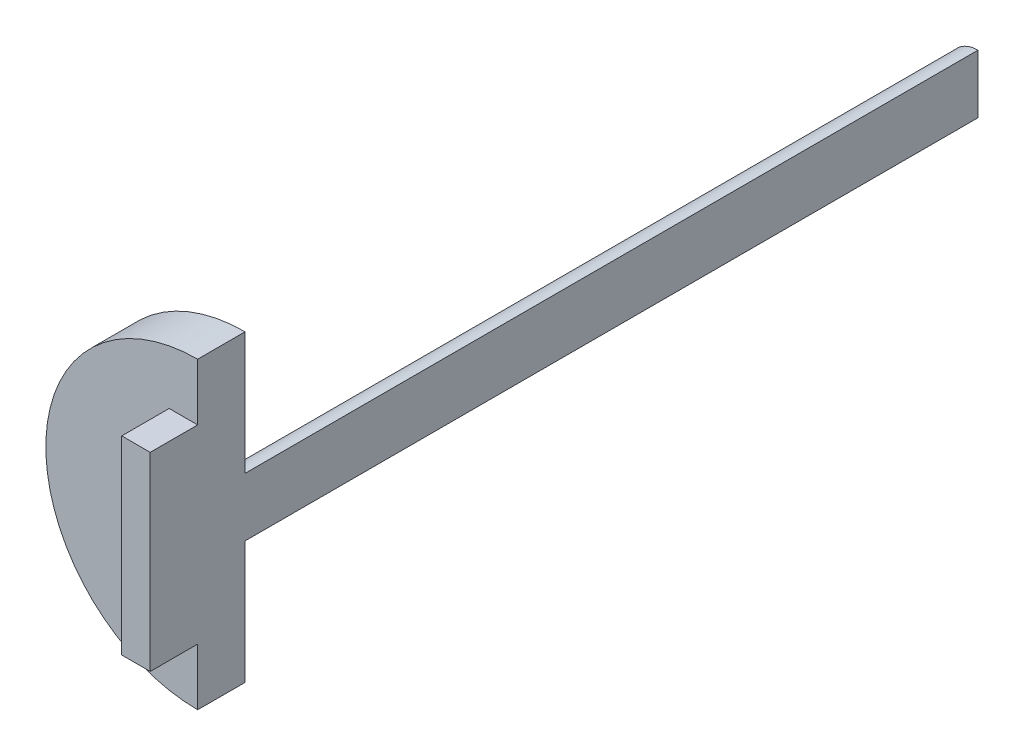
SolidWorks part; units mm, degrees
ref_plane "Plano frontal" through (0, 0, 0) normal (0, 0, 1) x (1, 0, 0)
ref_plane "Plano superior" through (0, 0, 0) normal (0, 1, 0) x (1, 0, 0)
ref_plane "Plano direito" through (0, 0, 0) normal (1, 0, 0) x (0, 0, -1)
sketch "Croquis11" plane through (0, 0, 0) normal (0, 0, 1) x (1, 0, 0)
  circle A0 centre (0, 0) radius 3.085
  dimension "D1" = 6.17
extrude "Saliente-Extruir2" add sketch "Croquis11" along normal blind 77.23
sketch "Croquis12" plane through (0, 0, 77.23) normal (0, 0, 1) x (1, 0, 0)
  circle A0 centre (0, 0) radius 16
  dimension "D1" = 32
extrude "Saliente-Extruir3" add sketch "Croquis12" along normal blind 5
sketch "Croquis13" plane through (0, 0, 82.23) normal (0, 0, 1) x (1, 0, 0)
  line L1 (-3, 10) -> (3, 10)
  line L2 (-3, 10) -> (-3, -10)
  line L3 (-3, -10) -> (3, -10)
  line L4 (3, 10) -> (3, -10)
  line L5 (-3, 10) -> (3, -10) construction
  line L6 (-3, -10) -> (3, 10) construction
  point P0 (0, 0)
  dimension "D1" = 6
  dimension "D2" = 20
extrude "Saliente-Extruir4" add sketch "Croquis13" along normal blind 5
sketch "Croquis14" plane through (0, 0, 87.23) normal (0, 0, 1) x (1, 0, 0)
  line L1 (0, -16) -> (16, -16)
  line L2 (0, -16) -> (0, 16)
  line L3 (0, 16) -> (16, 16)
  line L4 (16, -16) -> (16, 16)
  circle A0 centre (0, 0) radius 16 construction
extrude "Cortar-Extruir9" cut sketch "Croquis14" against normal up to surface (87.23 mm away) up to face at (3.085, 0, 0)
